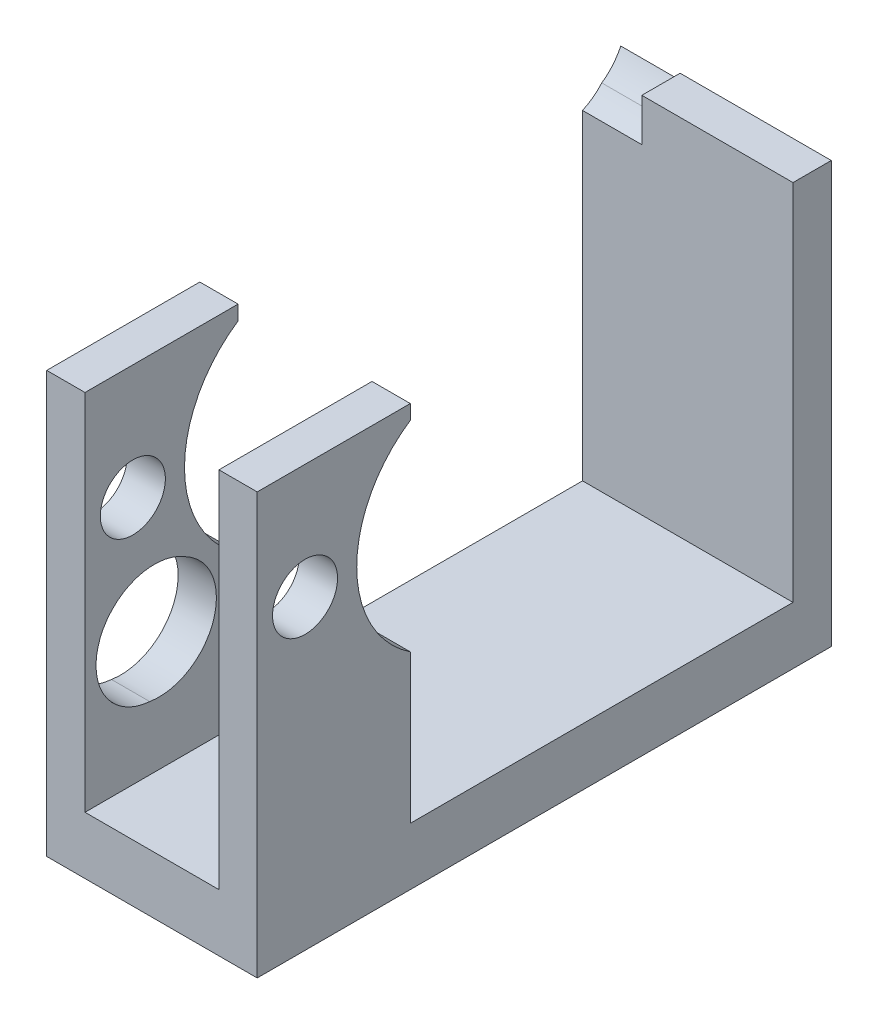
SolidWorks part; units mm, degrees
other "Preload Manual Lock Fork"
ref_plane "Front Plane" through (0, 0, 0) normal (0, 0, 1) x (1, 0, 0)
ref_plane "Top Plane" through (0, 0, 0) normal (0, 1, 0) x (1, 0, 0)
ref_plane "Right Plane" through (0, 0, 0) normal (1, 0, 0) x (0, 0, -1)
sketch3d "Rear lock ear sketch datum points"
  point P0 (-12, -45, -16)
  point P1 (-2, -45, -16)
  point P2 (-12, -35, -16)
ref_plane "Rear lock ear sketch plane" through (0, 0, -16) normal (0, 0, 1) x (1, 0, 0)
sketch "Rear lock ear sketch" plane through (0, 0, -16) normal (0, 0, 1) x (1, 0, 0)
  line L0 (-12, -45) -> (-10, -45)
  line L1 (-10, -45) -> (-10, -23)
  line L2 (-10, -23) -> (-12, -23)
  line L3 (-12, -23) -> (-12, -45)
extrude "Rear lock ear" add sketch "Rear lock ear sketch" along normal blind 8 separate body
sketch3d "Lock fork web sketch datum points"
  point P0 (-12, -45, -38)
  point P1 (-2, -45, -38)
  point P2 (-12, -35, -38)
ref_plane "Lock fork web sketch plane" through (0, 0, -38) normal (0, 0, 1) x (1, 0, 0)
sketch "Lock fork web sketch" plane through (0, 0, -38) normal (0, 0, 1) x (1, 0, 0)
  line L0 (-12, -45) -> (-1, -45)
  line L1 (-1, -45) -> (-1, -42)
  line L2 (-1, -42) -> (-12, -42)
  line L3 (-12, -42) -> (-12, -45)
extrude "Lock fork web" add sketch "Lock fork web sketch" along normal blind 30
sketch3d "Front lock ear sketch datum points"
  point P0 (-3, -45, -16)
  point P1 (7, -45, -16)
  point P2 (-3, -35, -16)
ref_plane "Front lock ear sketch plane" through (0, 0, -16) normal (0, 0, 1) x (1, 0, 0)
sketch "Front lock ear sketch" plane through (0, 0, -16) normal (0, 0, 1) x (1, 0, 0)
  line L0 (-3, -45) -> (-1, -45)
  line L1 (-1, -45) -> (-1, -23)
  line L2 (-1, -23) -> (-3, -23)
  line L3 (-3, -23) -> (-3, -45)
extrude "Front lock ear" add sketch "Front lock ear sketch" along normal blind 8
sketch3d "Fork mounting foot sketch datum points"
  point P0 (-12, -45, -38)
  point P1 (-2, -45, -38)
  point P2 (-12, -35, -38)
ref_plane "Fork mounting foot sketch plane" through (0, 0, -38) normal (0, 0, 1) x (1, 0, 0)
sketch "Fork mounting foot sketch" plane through (0, 0, -38) normal (0, 0, 1) x (1, 0, 0)
  line L0 (-12, -45) -> (-1, -45)
  line L1 (-1, -45) -> (-1, -23)
  line L2 (-1, -23) -> (-12, -23)
  line L3 (-12, -23) -> (-12, -45)
extrude "Fork mounting foot" add sketch "Fork mounting foot sketch" along normal blind 2
sketch3d "Coupling barrel clearance sketch datum points"
  point P0 (-12.1, -29, -19.5)
  point P1 (-12.1, -19, -19.5)
  point P2 (-12.1, -29, -9.5)
ref_plane "Coupling barrel clearance sketch plane" through (-12.1, 0, 0) normal (1, 0, 0) x (0, 0, -1)
sketch "Coupling barrel clearance sketch" plane through (-12.1, 0, 0) normal (1, 0, 0) x (0, 0, -1)
  circle A0 centre (19.5, -29) radius 6.3
extrude "Coupling barrel clearance" cut sketch "Coupling barrel clearance sketch" along normal blind 11.3
sketch3d "Service pin clearance 1 sketch datum points"
  point P0 (-12.1, -29, -10.5)
  point P1 (-12.1, -19, -10.5)
  point P2 (-12.1, -29, -0.5)
ref_plane "Service pin clearance 1 sketch plane" through (-12.1, 0, 0) normal (1, 0, 0) x (0, 0, -1)
sketch "Service pin clearance 1 sketch" plane through (-12.1, 0, 0) normal (1, 0, 0) x (0, 0, -1)
  circle A0 centre (10.5, -29) radius 1.7
extrude "Service pin clearance 1" cut sketch "Service pin clearance 1 sketch" along normal blind 2.3
sketch3d "Service pin clearance 2 sketch datum points"
  point P0 (-3.1, -29, -10.5)
  point P1 (-3.1, -19, -10.5)
  point P2 (-3.1, -29, -0.5)
ref_plane "Service pin clearance 2 sketch plane" through (-3.1, 0, 0) normal (1, 0, 0) x (0, 0, -1)
sketch "Service pin clearance 2 sketch" plane through (-3.1, 0, 0) normal (1, 0, 0) x (0, 0, -1)
  circle A0 centre (10.5, -29) radius 1.7
extrude "Service pin clearance 2" cut sketch "Service pin clearance 2 sketch" along normal blind 2.3
sketch3d "Motor head access 1-1 sketch datum points"
  point P0 (-12.1, -22.5, -34.765)
  point P1 (-12.1, -12.5, -34.765)
  point P2 (-12.1, -22.5, -24.765)
ref_plane "Motor head access 1-1 sketch plane" through (-12.1, 0, 0) normal (1, 0, 0) x (0, 0, -1)
sketch "Motor head access 1-1 sketch" plane through (-12.1, 0, 0) normal (1, 0, 0) x (0, 0, -1)
  circle A0 centre (34.765, -22.5) radius 3
extrude "Motor head access 1-1" cut sketch "Motor head access 1-1 sketch" along normal blind 3.2
sketch3d "Motor head access 1-5 sketch datum points"
  point P0 (-12.1, -35.7199, -11.8675)
  point P1 (-12.1, -25.7199, -11.8675)
  point P2 (-12.1, -35.7199, -1.8675)
ref_plane "Motor head access 1-5 sketch plane" through (-12.1, 0, 0) normal (1, 0, 0) x (0, 0, -1)
sketch "Motor head access 1-5 sketch" plane through (-12.1, 0, 0) normal (1, 0, 0) x (0, 0, -1)
  circle A0 centre (11.8675, -35.7199) radius 3
extrude "Motor head access 1-5" cut sketch "Motor head access 1-5 sketch" along normal blind 3.2
sketch3d "Motor head access 2-1 sketch datum points"
  point P0 (-12.1, -22, -35.25)
  point P1 (-12.1, -12, -35.25)
  point P2 (-12.1, -22, -25.25)
ref_plane "Motor head access 2-1 sketch plane" through (-12.1, 0, 0) normal (1, 0, 0) x (0, 0, -1)
sketch "Motor head access 2-1 sketch" plane through (-12.1, 0, 0) normal (1, 0, 0) x (0, 0, -1)
  circle A0 centre (35.25, -22) radius 3.05
extrude "Motor head access 2-1" cut sketch "Motor head access 2-1 sketch" along normal blind 3.2
sketch3d "Motor head access 2-5 sketch datum points"
  point P0 (-12.1, -35.6399, -11.625)
  point P1 (-12.1, -25.6399, -11.625)
  point P2 (-12.1, -35.6399, -1.625)
ref_plane "Motor head access 2-5 sketch plane" through (-12.1, 0, 0) normal (1, 0, 0) x (0, 0, -1)
sketch "Motor head access 2-5 sketch" plane through (-12.1, 0, 0) normal (1, 0, 0) x (0, 0, -1)
  circle A0 centre (11.625, -35.6399) radius 3.05
extrude "Motor head access 2-5" cut sketch "Motor head access 2-5 sketch" along normal blind 3.2
